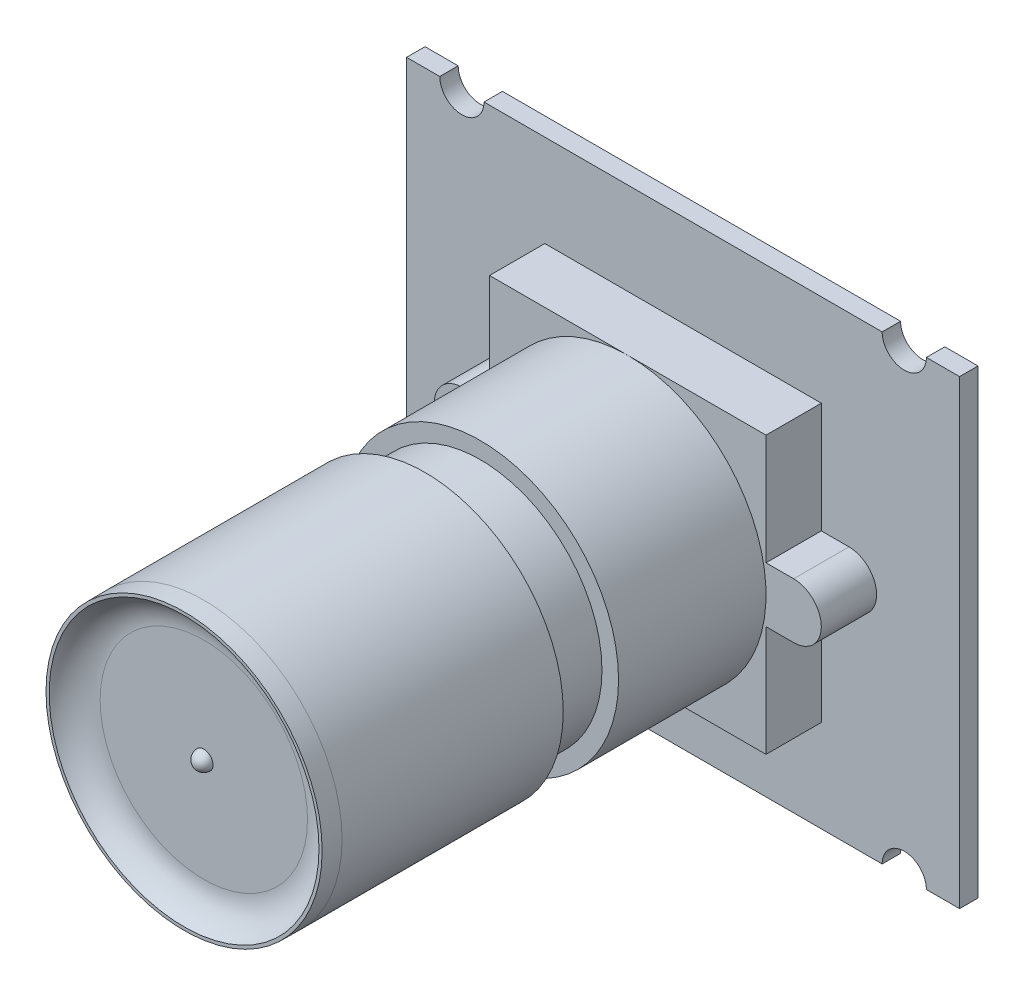
SolidWorks part; units mm, degrees
ref_plane "前视基准面" through (0, 0, 0) normal (0, 0, 1) x (1, 0, 0)
ref_plane "上视基准面" through (0, 0, 0) normal (0, 1, 0) x (1, 0, 0)
ref_plane "右视基准面" through (0, 0, 0) normal (1, 0, 0) x (0, 0, -1)
sketch "草图1" plane through (0, 0, 0) normal (0, 0, 1) x (1, 0, 0)
  line L0 (4.2, 8.956) -> (25.8, 8.956)
  line L1 (0, 8.956) -> (1.8, 8.956)
  line L2 (0, 8.956) -> (0, -16.044)
  line L3 (0, -16.044) -> (1.8, -16.044)
  line L4 (30, 8.956) -> (30, -16.044)
  line L5 (28.2, 8.956) -> (30, 8.956)
  line L6 (4.2, -16.044) -> (25.8, -16.044)
  line L7 (28.2, -16.044) -> (30, -16.044)
  arc A0 (1.8, 8.956) -> (4.2, 8.956) centre (3, 8.956) ccw
  arc A1 (25.8, 8.956) -> (28.2, 8.956) centre (27, 8.956) ccw
  arc A2 (28.2, -16.044) -> (25.8, -16.044) centre (27, -16.044) ccw
  arc A3 (4.2, -16.044) -> (1.8, -16.044) centre (3, -16.044) ccw
  dimension "D1" = 30
  dimension "D3" = 24
  dimension "D4" = 3
  dimension "D2" = 25
extrude "凸台-拉伸1" add sketch "草图1" along normal blind 1
sketch "草图2" plane through (0, 0, 1) normal (0, 0, 1) x (1, 0, 0)
  line L0 (0, 8.956) -> (0, -16.044) construction
  line L1 (30, -16.044) -> (30, 8.956) construction
  line L2 (6, -2.044) -> (24, -2.044)
  line L3 (6, -5.044) -> (24, -5.044)
  line L4 (0, -3.544) -> (30, -3.544) construction
  arc A0 (6, -2.044) -> (6, -5.044) centre (6, -3.544) ccw
  arc A1 (24, -5.044) -> (24, -2.044) centre (24, -3.544) ccw
  point P1 (0, -3.544)
  point P3 (30, -3.544)
  dimension "D1" = 6
  dimension "D2" = 6
extrude "凸台-拉伸2" add sketch "草图2" along normal blind 3
sketch "草图3" plane through (0, 0, 1) normal (0, 0, 1) x (1, 0, 0)
  line L0 (25.8, 8.956) -> (4.2, 8.956) construction
  line L1 (4.2, -16.044) -> (25.8, -16.044) construction
  line L2 (15, 8.956) -> (15, 3.956) construction
  line L3 (15, -11.044) -> (15, -16.044) construction
  line L4 (7.5, 3.956) -> (22.5, 3.956)
  line L5 (7.5, 3.956) -> (7.5, -11.044)
  line L6 (7.5, -11.044) -> (22.5, -11.044)
  line L7 (22.5, 3.956) -> (22.5, -11.044)
  point P0 (15, 8.956)
  point P1 (15, -16.044)
extrude "凸台-拉伸3" add sketch "草图3" along normal blind 3
sketch "草图4" plane through (0, 0, 4) normal (0, 0, 1) x (1, 0, 0)
  line L0 (0, -3.544) -> (30, -3.544) construction
  line L1 (0, 8.956) -> (0, -16.044) construction
  line L2 (30, -16.044) -> (30, 8.956) construction
  circle A0 centre (15, -3.544) radius 7.5
extrude "凸台-拉伸4" add sketch "草图4" along normal blind 8
sketch "草图5" plane through (0, 0, 12) normal (0, 0, 1) x (1, 0, 0)
  line L0 (0, -3.544) -> (30, -3.544) construction
  line L1 (0, 8.956) -> (0, -16.044) construction
  line L2 (30, -16.044) -> (30, 8.956) construction
  circle A0 centre (15, -3.544) radius 6.6
extrude "凸台-拉伸5" add sketch "草图5" along normal blind 3
sketch "草图6" plane through (0, 0, 15) normal (0, 0, 1) x (1, 0, 0)
  line L0 (0, -3.544) -> (30, -3.544) construction
  line L1 (0, 8.956) -> (0, -16.044) construction
  line L2 (30, -16.044) -> (30, 8.956) construction
ref_plane "基准面4" through (0, -3.544, 0) normal (0, -1, 0) x (-1, 0, 0)
sketch "草图7" plane through (0, -3.544, 0) normal (0, -1, 0) x (-1, 0, 0)
  line L0 (0, -15) -> (-30, -15) construction
  line L1 (-15, -15) -> (-7.5, -15)
  line L4 (-7.5, -15) -> (-7.5, -27)
  line L8 (-9.375, -27) -> (-14.5, -27)
  line L9 (-15, -22) -> (-15, -15)
  line L10 (-11.9375, -27) -> (-11.9375, -32.5524) construction
  line L11 (-7.5, -27) -> (-7.5095, -28.0708)
  line L12 (-7.5095, -28.0708) -> (-7.6812, -28.0708)
  line L13 (-15, -22) -> (-15, -27)
  line L14 (-15, -27) -> (-15, -27.5)
  arc A2 (-7.6812, -28.0708) -> (-9.375, -27) centre (-9.375, -28.875) ccw
  arc A4 (-15, -27.5) -> (-14.5, -27) centre (-15, -27) ccw
  dimension "D1" = 7.5
  dimension "D2" = 12
revolve "旋转2" add sketch "草图7" angle 360 about L9
